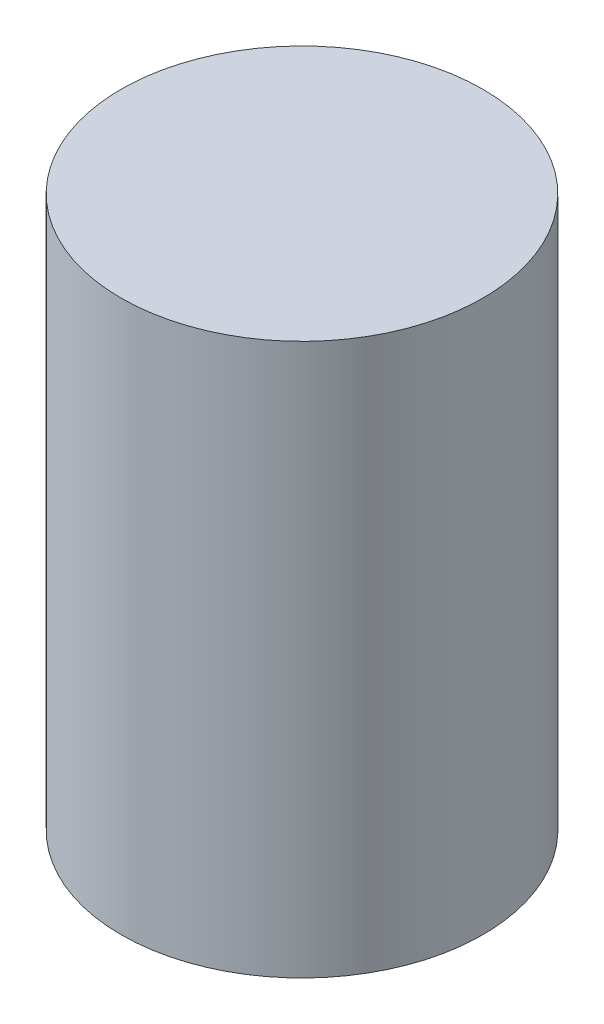
SolidWorks part; units mm, degrees
ref_plane "Front Plane" through (0, 0, 0) normal (0, 0, 1) x (1, 0, 0)
ref_plane "Top Plane" through (0, 0, 0) normal (0, 1, 0) x (1, 0, 0)
ref_plane "Right Plane" through (0, 0, 0) normal (1, 0, 0) x (0, 0, -1)
sketch "Sketch1" plane through (0, 0, 0) normal (0, 1, 0) x (1, 0, 0)
  circle A0 centre (0, 0) radius 50
  dimension "D1" = 100
extrude "Boss-Extrude1" add sketch "Sketch1" along normal blind 152.4
